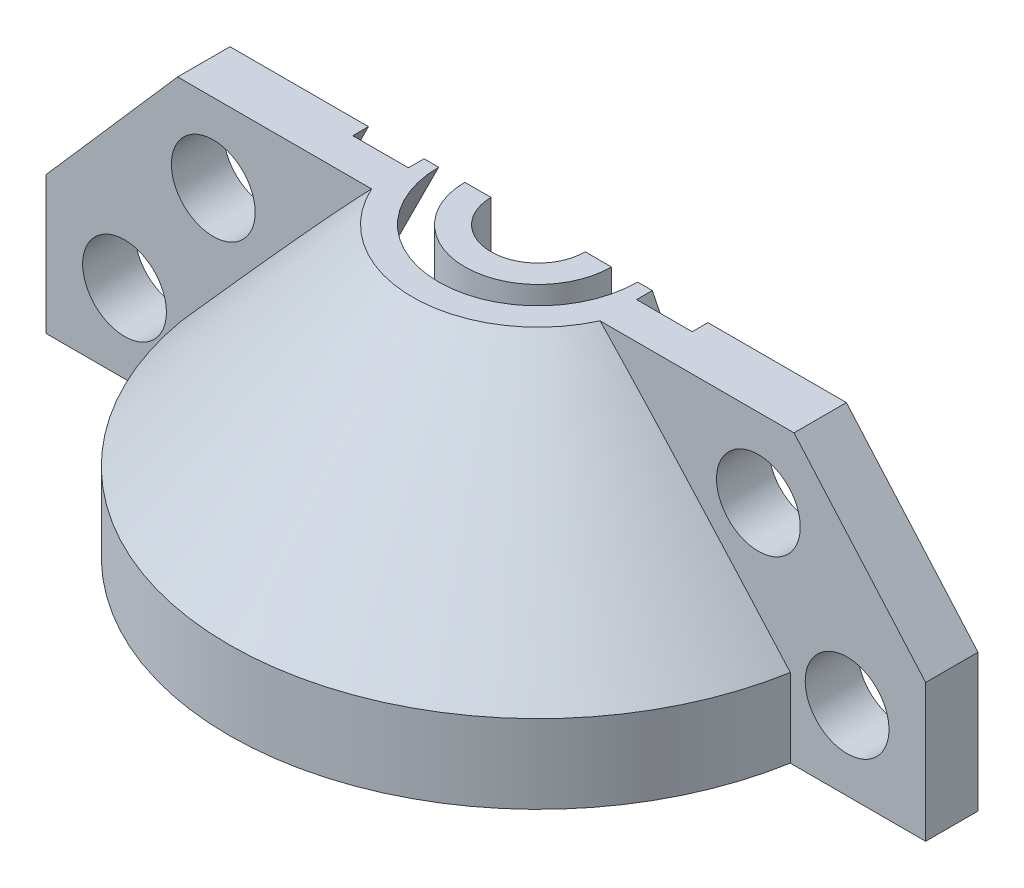
SolidWorks part; units mm, degrees
ref_plane "Front Plane" through (0, 0, 0) normal (0, 0, 1) x (1, 0, 0)
ref_plane "Top Plane" through (0, 0, 0) normal (0, 1, 0) x (1, 0, 0)
ref_plane "Right Plane" through (0, 0, 0) normal (1, 0, 0) x (0, 0, -1)
sketch "Sketch1" plane through (0, 0, 0) normal (0, 0, 1) x (1, 0, 0)
  line L0 (0, 0) -> (0, 12.4672) construction
  line L1 (-1.8, 0) -> (-1.8, 8)
  line L2 (-1.8, 0) -> (-2.8, 0)
  line L3 (-1.8, 8) -> (-2.8, 8)
  line L4 (-2.8, 0) -> (-2.8, 8)
  line L5 (-3.8, 8) -> (-7.8, 0)
  line L6 (-7.8, 0) -> (-10.8, 0)
  line L7 (-10.8, 0) -> (-3.8, 8)
  line L9 (-10.8, 0) -> (-1.8, 0)
  line L10 (-10.8, 0) -> (-10.8, -3)
  line L11 (-1.8, 0) -> (-1.8, -3)
  line L12 (-10.8, -3) -> (-1.8, -3)
  line L13 (-3.8, 8) -> (-2.8, 8) construction
  dimension "D1" = 1.8
  dimension "D2" = 1
  dimension "D3" = 3
  dimension "D4" = 1
  dimension "D5" = 8
  dimension "D6" = 5
  dimension "D7" = 3
revolve "Revolve1" add sketch "Sketch1" angle 180 about L0
sketch "Sketch2" plane through (0, 0, 0) normal (0, 0, -1) x (-1, 0, 0)
  line L0 (-10.8, -3) -> (-16.8, -3)
  line L1 (-10.8, -3) -> (-10.8, 0)
  line L2 (-16.8, -3) -> (-16.8, 2.2544)
  line L4 (-3.8, 8) -> (-11.7726, 8)
  line L5 (-11.7726, 8) -> (-16.8, 2.2544)
  line L6 (-10.8, 0) -> (-3.8, 8) construction
  line L7 (-10.8, 0) -> (-3.8, 8)
  line L8 (-10.4113, 5) -> (-8.1536, 3.0245) construction
  line L9 (-10.4113, 5) -> (-12.669, 6.9755) construction
  line L10 (0, 0) -> (0, 11.7241) construction
  line L11 (10.4113, 5) -> (12.669, 6.9755) construction
  line L12 (10.4113, 5) -> (8.1536, 3.0245) construction
  line L13 (10.8, 0) -> (3.8, 8)
  line L14 (11.7726, 8) -> (16.8, 2.2544)
  line L15 (3.8, 8) -> (11.7726, 8)
  line L16 (16.8, -3) -> (16.8, 2.2544)
  line L17 (10.8, -3) -> (10.8, 0)
  line L18 (10.8, -3) -> (16.8, -3)
  circle A0 centre (-10.4113, 5) radius 1.6
  circle A2 centre (-13.8, 0) radius 1.6
  circle A3 centre (13.8, 0) radius 1.6
  circle A4 centre (10.4113, 5) radius 1.6
  dimension "D1" = 3.2
  dimension "D2" = 3
  dimension "D3" = 3
  dimension "D4" = 6
  dimension "D5" = 3
  dimension "D6" = 3
  dimension "D7" = 3
extrude "Boss-Extrude1" add sketch "Sketch2" against normal blind 2 separate body
sketch "Sketch3" plane through (0, 0, 0) normal (0, 0, -1) x (-1, 0, 0)
  line L0 (-11.8, -3) -> (-11.8, 0)
  line L1 (-16.8, -3) -> (-10.8, -3) construction
  line L2 (-11.8, 0) -> (-4.8, 8)
  line L3 (-3.8, 8) -> (-11.7726, 8) construction
  line L4 (0, 0) -> (0, 11.82) construction
  line L10 (-10.8, 0) -> (-3.8, 8)
  line L11 (-3.8, 8) -> (-11.7726, 8)
  line L12 (-11.7726, 8) -> (-16.8, 2.2544)
  line L13 (-16.8, 2.2544) -> (-16.8, -3)
  line L14 (-16.8, -3) -> (-10.8, -3)
  line L15 (-10.8, -3) -> (-10.8, 0)
  line L16 (-10.8, 0) -> (-3.8, 8)
  line L17 (-3.8, 8) -> (-4.8, 8)
  line L20 (-11.8, -3) -> (-10.8, -3)
  line L21 (-10.8, -3) -> (-10.8, 0)
  dimension "D2" = 1
  dimension "D3" = 1
  dimension "D1" = 0
revolve "Revolve2" add sketch "Sketch3" angle 180 about L4
sketch "Sketch4" plane through (0, 0, 0) normal (0, 0, -1) x (-1, 0, 0)
  line L0 (-6.2597, 8) -> (-4.5826, 8) construction
  line L1 (-3.8, 8) -> (-11.7726, 8) construction
  line L2 (-4.5826, 8) -> (-8.9326, -0.7) construction
  line L3 (-8.9326, -0.7) -> (-1.8, -0.7) construction
  line L4 (-1.8, 8) -> (-1.8, -3) construction
  line L5 (-1.8, -0.7) -> (-1.8, -2.2) construction
  line L6 (-1.8, -2.2) -> (-11.3597, -2.2) construction
  line L7 (-11.3597, -2.2) -> (-6.2597, 8) construction
  line L8 (0, 0) -> (0, 2.5831) construction
  line L9 (-3.8, 8) -> (-7.8, 0) construction
  line L10 (-2.8, 0) -> (-7.8, 0) construction
  line L11 (11.3597, -2.2) -> (6.2597, 8) construction
  line L12 (1.8, -2.2) -> (11.3597, -2.2) construction
  line L13 (1.8, -0.7) -> (1.8, -2.2) construction
  line L14 (8.9326, -0.7) -> (1.8, -0.7) construction
  line L15 (4.5826, 8) -> (8.9326, -0.7) construction
  line L16 (6.2597, 8) -> (4.5826, 8) construction
  line L17 (-11.6833, -2.4) -> (-6.3833, 8.2)
  line L18 (-6.3833, 8.2) -> (-4.259, 8.2)
  line L19 (-4.259, 8.2) -> (-8.609, -0.5)
  line L20 (-8.609, -0.5) -> (-1.6, -0.5)
  line L21 (-1.6, -0.5) -> (-1.6, -2.4)
  line L22 (-1.6, -2.4) -> (-11.6833, -2.4)
  line L32 (11.6833, -2.4) -> (6.3833, 8.2)
  line L33 (6.3833, 8.2) -> (4.259, 8.2)
  line L34 (4.259, 8.2) -> (8.609, -0.5)
  line L35 (8.609, -0.5) -> (1.6, -0.5)
  line L36 (1.6, -0.5) -> (1.6, -2.4)
  line L37 (1.6, -2.4) -> (11.6833, -2.4)
  line L38 (-2.4, -0.5) -> (-2.4, -2.4)
  line L39 (2.4, -0.5) -> (2.4, -2.4)
  line L40 (1.8, 8) -> (1.8, -3) construction
  line M9 (-3.8, 8) -> (-11.7726, 8)
  dimension "D1" = 1.5
  dimension "D2" = 1.5
  dimension "D3" = 0.7
  dimension "D4" = 0.7
  dimension "D7" = 0.6
  dimension "D8" = 0.6
  dimension "D5" = 0.2
  dimension "D6" = 0.2
extrude "Cut-Extrude1" cut sketch "Sketch4" against normal blind 0.6 contours L38 L20 L19 L17 L22 M9 | L35 L39 L37 L32 L33 L34
